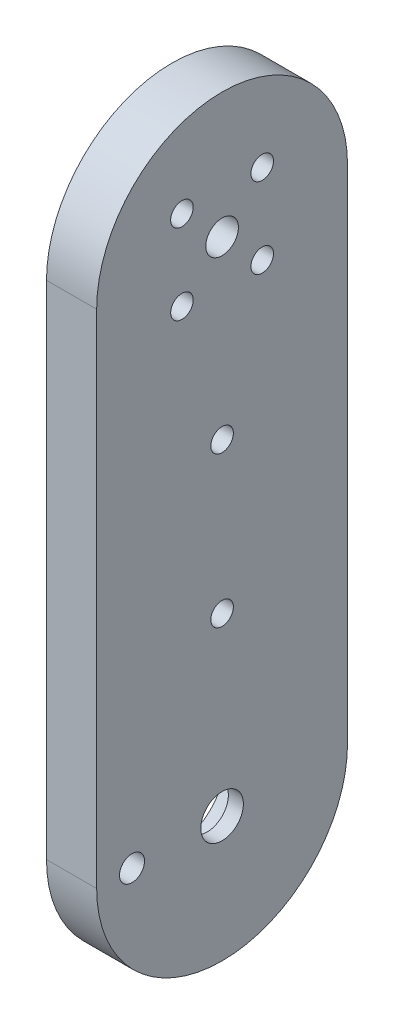
SolidWorks part; units mm, degrees
material "ABS"
ref_plane "Alzado" through (0, 0, 0) normal (0, 0, 1) x (1, 0, 0)
ref_plane "Planta" through (0, 0, 0) normal (0, 1, 0) x (1, 0, 0)
ref_plane "Vista lateral" through (0, 0, 0) normal (1, 0, 0) x (0, 0, -1)
sketch "Croquis1" plane through (0, 0, 0) normal (1, 0, 0) x (0, 0, -1)
  line L0 (-25, 0) -> (-25, -85)
  line L1 (-25, -85) -> (25, -85)
  line L2 (25, -85) -> (25, 0)
  line L4 (-8, -8) -> (8, -8) construction
  line L5 (-8, -8) -> (-8, 8) construction
  line L6 (-8, 8) -> (8, 8) construction
  line L7 (8, -8) -> (8, 8) construction
  line L8 (-8, -8) -> (8, 8) construction
  line L9 (-8, 8) -> (8, -8) construction
  arc A0 (25, 0) -> (-25, 0) centre (0, 0) ccw
  circle A1 centre (0, 0) radius 3.25
  circle A2 centre (-8, 8) radius 2.25
  circle A3 centre (8, 8) radius 2.25
  circle A4 centre (8, -8) radius 2.25
  circle A5 centre (-8, -8) radius 2.25
  dimension "D1" = 50
  dimension "D3" = 6.5
  dimension "D6" = 4.5
  dimension "D2" = 85
  dimension "D4" = 16
  dimension "D5" = 16
extrude "Saliente-Extruir1" add sketch "Croquis1" along normal blind 10
sketch "Croquis2" plane through (10, 0, 0) normal (1, 0, 0) x (0, 0, -1)
  line L0 (0, 0) -> (0, -100) construction
  line L1 (-25, -100) -> (-25, -85)
  line L2 (-25, -85) -> (25, -85)
  line L3 (25, -85) -> (25, -100)
  arc A0 (-25, -100) -> (25, -100) centre (0, -100) ccw
  dimension "D1" = 100
extrude "Saliente-Extruir2" add sketch "Croquis2" against normal up to surface (10 mm away) up to face at (0, -36.25, 0)
sketch "Croquis3" plane through (0, 0, 0) normal (-1, 0, 0) x (0, 0, 1)
  line L0 (-25, -50) -> (25, -50) construction
  line L1 (-25, -100) -> (-25, 0) construction
  line L2 (25, 0) -> (25, -100) construction
  line L3 (0, -65) -> (0, -35) construction
  circle A0 centre (0, -35) radius 2.25
  circle A1 centre (0, -65) radius 2.25
  point P10 (0, -50)
  dimension "D2" = 4.5
  dimension "D1" = 30
extrude "Cortar-Extruir1" cut sketch "Croquis3" against normal through all
sketch "Croquis4" plane through (0, 0, 0) normal (-1, 0, 0) x (0, 0, 1)
  circle A0 centre (0, -100) radius 10.9
  dimension "D1" = 21.8
extrude "Cortar-Extruir2" cut sketch "Croquis4" against normal blind 7
sketch "Croquis5" plane through (7, 0, 0) normal (-1, 0, 0) x (0, 0, 1)
  circle A0 centre (0, -100) radius 4.25
  dimension "D1" = 8.5
extrude "Cortar-Extruir3" cut sketch "Croquis5" against normal through all
sketch "Croquis6" plane through (0, 0, 0) normal (-1, 0, 0) x (0, 0, 1)
  line L0 (10.9, -100) -> (17.95, -100) construction
  line L1 (17.95, -100) -> (25, -100) construction
  circle A0 centre (0, -100) radius 10.9 construction
  circle A1 centre (0, -100) radius 10.9 construction
  circle A2 centre (17.95, -100) radius 2.5
  dimension "D1" = 5
extrude "Cortar-Extruir4" cut sketch "Croquis6" against normal through all
